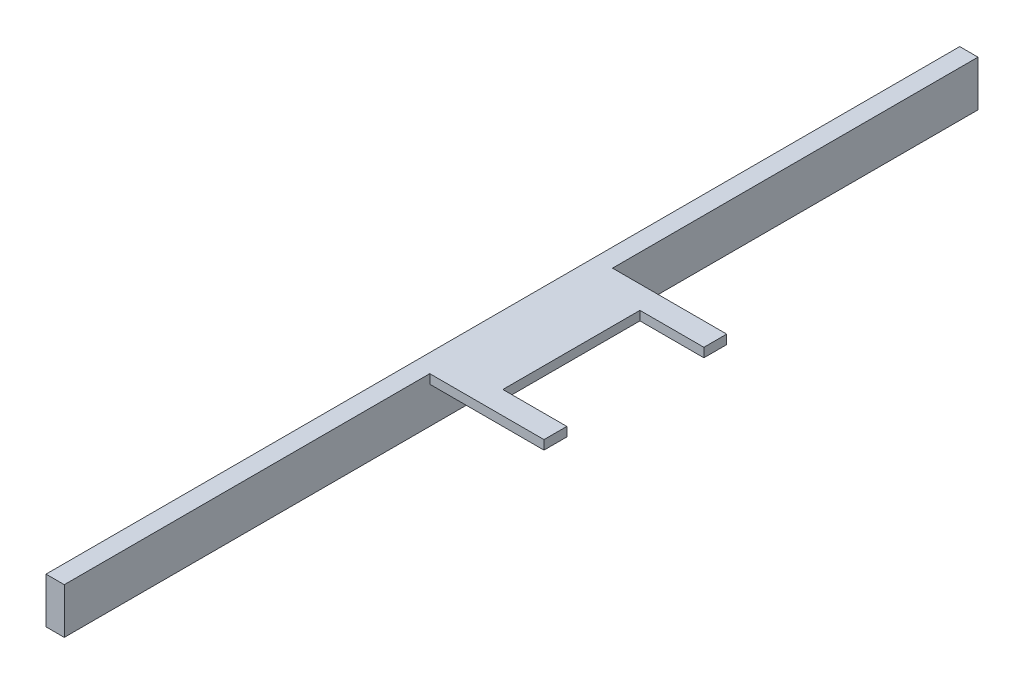
SolidWorks part; units mm, degrees
ref_plane "Alzado" through (0, 0, 0) normal (0, 0, 1) x (1, 0, 0)
ref_plane "Planta" through (0, 0, 0) normal (0, 1, 0) x (1, 0, 0)
ref_plane "Vista lateral" through (0, 0, 0) normal (1, 0, 0) x (0, 0, -1)
sketch "Croquis1" plane through (0, 0, 0) normal (0, 0, 1) x (1, 0, 0)
  line L0 (2, 5) -> (2, 4) construction
  line L1 (0, 0) -> (2, 0)
  line L2 (0, 0) -> (0, 5)
  line L3 (0, 5) -> (2, 5)
  line L4 (2, 0) -> (2, 4)
  line L5 (2, 5) -> (14.5, 5)
  line L7 (2, 4) -> (14.5, 4)
  line L8 (14.5, 5) -> (14.5, 4)
  dimension "D1" = 4
  dimension "D2" = 5
  dimension "D3" = 12.5
  dimension "D4" = 2
extrude "Saliente-Extruir1" add sketch "Croquis1" along normal blind 100
sketch "Croquis2" plane through (0, 5, 0) normal (0, 1, 0) x (1, 0, 0)
  line L0 (14.5, -100) -> (14.5, 0) construction
  line L1 (14.5, -57.5) -> (7.5, -57.5)
  line L2 (14.5, -57.5) -> (14.5, -42.5)
  line L3 (14.5, -42.5) -> (7.5, -42.5)
  line L4 (7.5, -57.5) -> (7.5, -42.5)
  line L5 (7.5, -50) -> (0, -50) construction
  line L6 (0, -100) -> (0, 0) construction
  line L7 (2, -100) -> (2, 0) construction
  line L9 (14.5, 0) -> (2, 0)
  line L10 (14.5, 0) -> (14.5, -40)
  line L11 (14.5, -40) -> (2, -40)
  line L12 (2, 0) -> (2, -40)
  line L13 (14.5, -100) -> (2, -100)
  line L14 (14.5, -100) -> (14.5, -60)
  line L15 (14.5, -60) -> (2, -60)
  line L16 (2, -100) -> (2, -60)
  dimension "D1" = 5.5
  dimension "D2" = 15
  dimension "D3" = 40
extrude "Cortar-Extruir1" cut sketch "Croquis2" against normal blind 11
